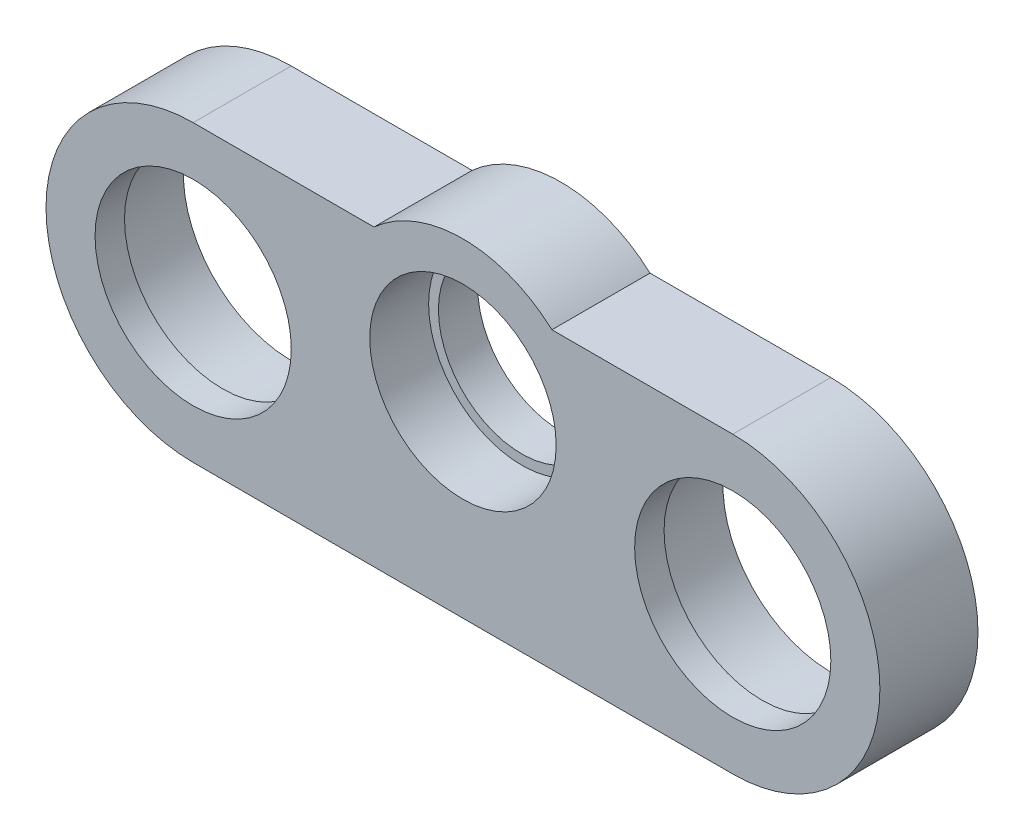
SolidWorks part; units mm, degrees
ref_plane "Plan de face" through (0, 0, 0) normal (0, 0, 1) x (1, 0, 0)
ref_plane "Plan de dessus" through (0, 0, 0) normal (0, 1, 0) x (1, 0, 0)
ref_plane "Plan de droite" through (0, 0, 0) normal (1, 0, 0) x (0, 0, -1)
sketch "Sketch1" plane through (0, 0, 0) normal (0, 0, 1) x (1, 0, 0)
  line L0 (27.5, 0) -> (-27.5, 0) construction
  line L1 (27.5, -15) -> (-27.5, -15)
  line L2 (27.5, 15) -> (-27.5, 15)
  line L3 (0, 5) -> (0, 0) construction
  arc A0 (27.5, -15) -> (27.5, 15) centre (27.5, 0) ccw
  arc A1 (-27.5, 15) -> (-27.5, -15) centre (-27.5, 0) ccw
  circle A2 centre (-27.5, 0) radius 11
  circle A3 centre (27.5, 0) radius 11
  circle A5 centre (0, 5) radius 9.5
  circle A6 centre (0, 5) radius 13.5
  point P2 (0, 0)
  dimension "D1" = 22
  dimension "D2" = 22
  dimension "D3" = 19
  dimension "D4" = 30
  dimension "D7" = 4
  dimension "D5" = 55
  dimension "D6" = 5
extrude "Boss-Extrude1" add sketch "Sketch1" along normal blind 10 contours L2 A6 A5 | A6 L2 A1 L1 A0 A3 A2 | L2 A6
sketch "Sketch2" plane through (0, 0, 10) normal (0, 0, 1) x (1, 0, 0)
  circle A0 centre (-27.5, 0) radius 11
  circle A2 centre (27.5, 0) radius 11
  circle A6 centre (-27.5, 0) radius 10
  circle A8 centre (27.5, 0) radius 10
  circle A9 centre (-27.5, 0) radius 11 construction
  circle A10 centre (27.5, 0) radius 11 construction
  dimension "D1" = 1
  dimension "D3" = 1
extrude "Boss-Extrude2" add sketch "Sketch2" against normal blind 3
sketch "Sketch4" plane through (0, 0, 0) normal (0, 0, -1) x (-1, 0, 0)
  circle A0 centre (0, 5) radius 9.5
  circle A1 centre (0, 5) radius 8.5
  circle A3 centre (0, 5) radius 9.5 construction
  dimension "D1" = 1
extrude "Boss-Extrude3" add sketch "Sketch4" against normal blind 4
